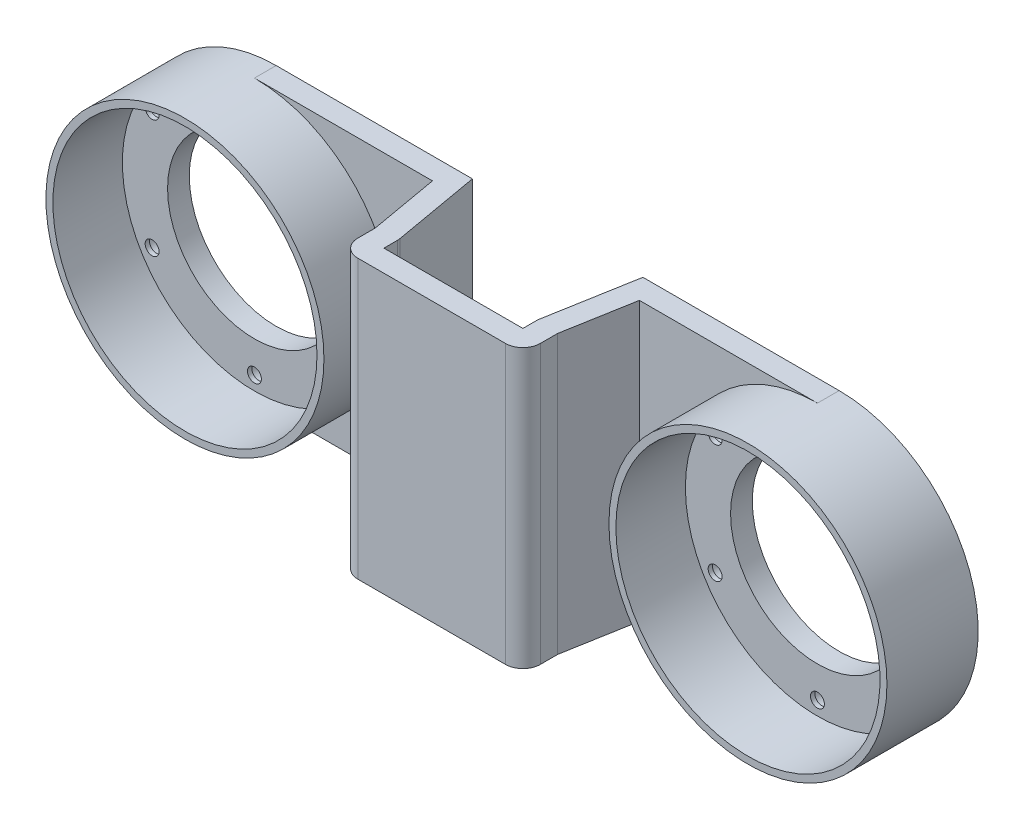
SolidWorks part; units mm, degrees
ref_plane "Front Plane" through (0, 0, 0) normal (0, 0, 1) x (1, 0, 0)
ref_plane "Top Plane" through (0, 0, 0) normal (0, 1, 0) x (1, 0, 0)
ref_plane "Right Plane" through (0, 0, 0) normal (1, 0, 0) x (0, 0, -1)
sketch "Sketch1" plane through (0, 0, 0) normal (0, 0, 1) x (1, 0, 0)
  line L0 (0, 0) -> (0, 41.85) construction
  line L1 (80, -40) -> (0, -40)
  line L2 (0, 0) -> (81, 0) construction
  line L3 (81, 0) -> (81, 40) construction
  line L4 (162, 0) -> (173.6469, 43.4667) construction
  line L5 (162, 0) -> (162, 45) construction
  line L8 (80, 40) -> (80, -40) construction
  line L12 (82, 40) -> (82, -50.6936) construction
  line L14 (82, 40) -> (80, 40)
  line L15 (82, -40) -> (80, -40)
  line L16 (80, 40) -> (0, 40)
  line L17 (82, -40) -> (162, -40)
  line L18 (82, 40) -> (162, 40)
  arc A20 (25, 0) -> (-25, 0) centre (0, 0) ccw
  arc A21 (-25, 0) -> (25, 0) centre (0, 0) ccw
  arc A58 (0, 40) -> (0, -40) centre (0, 0) ccw
  arc A59 (162, 40) -> (162, -40) centre (162, 0) cw
  arc A60 (187, 0) -> (137, 0) centre (162, 0) cw
  arc A61 (137, 0) -> (187, 0) centre (162, 0) cw
  circle A62 centre (0, 0) radius 34 construction
  circle A63 centre (0, 34) radius 2
  circle A64 centre (29.4449, 17) radius 2
  circle A65 centre (29.4449, -17) radius 2
  circle A66 centre (0, -34) radius 2
  circle A67 centre (-29.4449, -17) radius 2
  circle A68 centre (-29.4449, 17) radius 2
  circle A69 centre (162, -34) radius 2
  circle A70 centre (162, 0) radius 34 construction
  circle A71 centre (191.4449, 17) radius 2
  circle A72 centre (191.4449, -17) radius 2
  circle A73 centre (132.5551, -17) radius 2
  circle A74 centre (132.5551, 17) radius 2
  circle A75 centre (162, 34) radius 2
  point P18 (0, 0)
  point P30 (162, 0)
  point P113 (81, -40)
  point P118 (81, -40)
  point P119 (81, -40)
  point P120 (81, -40)
  dimension "D1" = 25
  dimension "D2" = 80
  dimension "D3" = 4
  dimension "D7" = 80
  dimension "D4" = 6
  dimension "D5" = 81
extrude "Boss-Extrude1" add sketch "Sketch1" along normal mid plane 50
sketch "Sketch2" plane through (0, 0, -25) normal (0, 0, -1) x (-1, 0, 0)
  line L0 (-81, -40) -> (-81, 40) construction
  line L1 (-162, 0) -> (-162, 34) construction
  line L2 (0, 0) -> (-3, 0) construction
  line L3 (0, 0) -> (0, 34) construction
  line L4 (-162, 0) -> (-159, 0) construction
  line L5 (-162, 25) -> (-162, -25) construction
  circle A5 centre (-162, 0) radius 34 construction
  circle A8 centre (-162, 34) radius 3
  circle A26 centre (-132.5551, 17) radius 3
  circle A27 centre (-132.5551, -17) radius 3
  circle A28 centre (-162, -34) radius 3
  circle A29 centre (-191.4449, -17) radius 3
  circle A30 centre (-191.4449, 17) radius 3
  circle A31 centre (0, 0) radius 34 construction
  circle A32 centre (29.4449, 17) radius 3
  circle A33 centre (29.4449, -17) radius 3
  circle A34 centre (0, -34) radius 3
  circle A35 centre (-29.4449, -17) radius 3
  circle A36 centre (-29.4449, 17) radius 3
  circle A37 centre (0, 34) radius 3
  circle A38 centre (-162, 0) radius 25 construction
  point P19 (-162, 0)
  point P20 (0, 0)
  point P34 (0, 0)
  point P35 (-162, 0)
  dimension "D1" = 68
  dimension "D2" = 6
extrude "Cut-Extrude2" cut sketch "Sketch2" against normal blind 5
sketch "Sketch5" plane through (0, 0, 0) normal (0, 1, 0) x (1, 0, 0)
  line L0 (61, -5) -> (54.75, -5) construction
  line L2 (61, -0.7032) -> (61, -5)
  line L3 (54.75, -1.25) -> (51.2235, 18.75)
  line L4 (107.25, -1.25) -> (110.7765, 18.75)
  line L6 (61, -0.7032) -> (56.4678, 25)
  line L8 (-40, 18.75) -> (-40, -25)
  line L13 (81, -25) -> (81, 25) construction
  line L14 (162, 25) -> (0, 25) construction
  line L15 (-40, 25) -> (-40, -25) construction
  line L16 (101, -0.7032) -> (105.5322, 25)
  line L18 (101, -0.7032) -> (101, -5)
  line L23 (162, -25) -> (0, -25) construction
  line L24 (162, 25) -> (0, 25) construction
  line L26 (61, 25) -> (101, 25) construction
  line L32 (54.75, -1.25) -> (54.75, -11.25)
  line L33 (-40, 18.75) -> (51.2235, 18.75)
  line L35 (0, 25) -> (-40, 25) construction
  line L36 (61, -5) -> (101, -5)
  line L38 (202, 18.75) -> (110.7765, 18.75)
  line L39 (107.25, -1.25) -> (107.25, -11.25)
  line L40 (202, 18.75) -> (202, -25)
  line L41 (101, 25) -> (101, -5) construction
  line L42 (54.75, -11.25) -> (107.25, -11.25)
  line L44 (56.4678, 25) -> (105.5322, 25)
  line L45 (-40, -25) -> (202, -25)
  point P18 (81, -5)
  point P25 (81, -5)
  dimension "D3" = 6.25
  dimension "D2" = 6.25
  dimension "D1" = 90
  dimension "D4" = 40
  dimension "D5" = 6.25
  dimension "D6" = 30
  dimension "D7" = 10
  dimension "D8" = 100
  dimension "D9" = 6.25
extrude "Cut-Extrude3" cut sketch "Sketch5" against normal mid plane 325
ref_plane "Plane1" through (100, 0, 0) normal (1, 0, 0) x (0, 0, -1)
sketch "Sketch6" plane through (0, 0, -18.75) normal (0, 0, 1) x (1, 0, 0)
  line L0 (81, 40) -> (81, -40) construction
  line L1 (54.75, 40) -> (107.25, 40) construction
  line L2 (107.25, -40) -> (54.75, -40) construction
  circle A0 centre (0, 0) radius 38
  circle A1 centre (0, 0) radius 40
  arc A2 (0, 40) -> (0, -40) centre (0, 0) ccw construction
  circle A3 centre (162, 0) radius 40
  circle A4 centre (162, 0) radius 38
  dimension "D1" = 76
extrude "Boss-Extrude2" add sketch "Sketch6" along normal blind 20
fillet "Fillet1" radius 5 4 edges at (107.25, 0, 11.25) (54.75, 0, 11.25) (101, 0, 0.7032) (61, 0, 0.7032)
equation "\"c\"=6.25"
equation "\"D5@Sketch5\"=\"c\""
equation "\"D2@Sketch5\"=\"c\""
equation "\"D3@Sketch5\"=\"c\""
